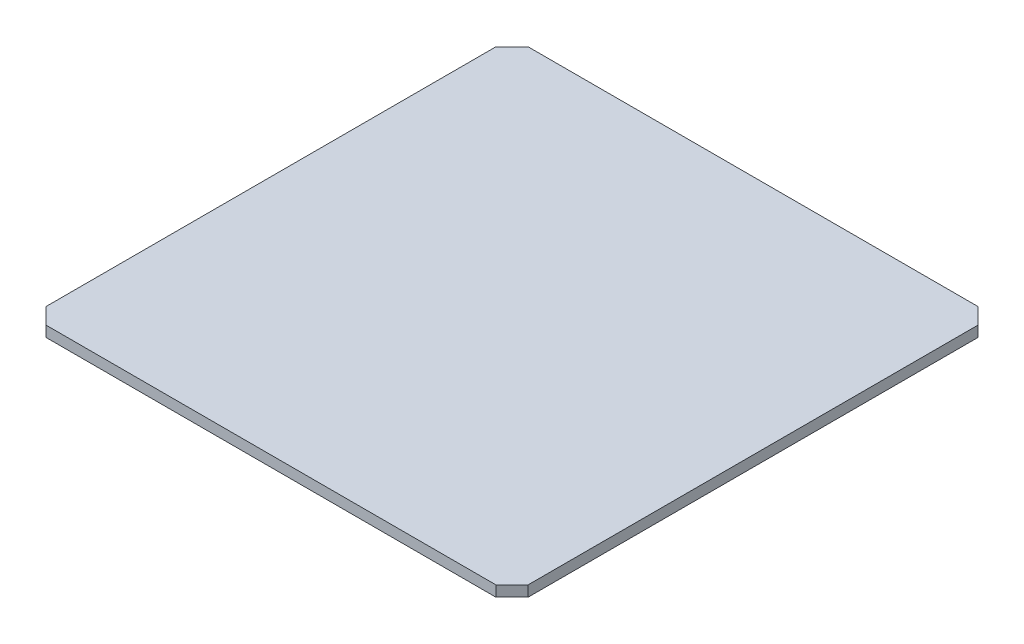
SolidWorks part; units mm, degrees
ref_plane "Front Plane" through (0, 0, 0) normal (0, 0, 1) x (1, 0, 0)
ref_plane "Top Plane" through (0, 0, 0) normal (0, 1, 0) x (1, 0, 0)
ref_plane "Right Plane" through (0, 0, 0) normal (1, 0, 0) x (0, 0, -1)
sketch "Esquisse1" plane through (0, 0, 0) normal (0, 1, 0) x (1, 0, 0)
  line L0 (45, 45) -> (-45, -45) construction
  line L1 (-42, 45) -> (42, 45)
  line L2 (-45, 42) -> (-45, -42)
  line L3 (-42, -45) -> (42, -45)
  line L4 (45, 42) -> (45, -42)
  line L5 (-45, 42) -> (-42, 45)
  line L6 (42, 45) -> (45, 42)
  line L7 (42, -45) -> (45, -42)
  line L8 (-45, -42) -> (-42, -45)
  point P0 (-45, 45)
  point P1 (45, -45)
  point P7 (-42, 38.7285)
  dimension "D1" = 90
extrude "Boss.-Extru.1" add sketch "Esquisse1" along normal blind 2
sketch "Esquisse2" plane through (0, 0, 0) normal (0, -1, 0) x (1, 0, 0)
  line L0 (24.5, 24.5) -> (-24.5, -24.5) construction
  line L1 (-24.5, 24.5) -> (24.5, 24.5) construction
  line L2 (-24.5, 24.5) -> (-24.5, -24.5) construction
  line L3 (-24.5, -24.5) -> (24.5, -24.5) construction
  line L4 (24.5, 24.5) -> (24.5, -24.5) construction
  circle A0 centre (-24.5, 24.5) radius 4
  circle A1 centre (24.5, 24.5) radius 4
  circle A2 centre (-24.5, -24.5) radius 4
  circle A3 centre (24.5, -24.5) radius 4
  circle A4 centre (-24.5, 24.5) radius 1.5
  circle A5 centre (24.5, 24.5) radius 1.5
  circle A6 centre (24.5, -24.5) radius 1.5
  circle A7 centre (-24.5, -24.5) radius 1.5
  dimension "D1" = 3
  dimension "D3" = 8
  dimension "D2" = 20.5
extrude "Boss.-Extru.2" add sketch "Esquisse2" along normal blind 6.25
sketch "Esquisse3" plane through (0, 0, 0) normal (0, -1, 0) x (1, 0, 0)
  line L0 (-7.5, -3.75) -> (7.5, 3.75) construction
  line L1 (-7.5, 3.75) -> (7.5, 3.75)
  line L2 (-7.5, 3.75) -> (-7.5, -3.75)
  line L3 (-7.5, -3.75) -> (7.5, -3.75)
  line L4 (7.5, 3.75) -> (7.5, -3.75)
  dimension "D1" = 15
  dimension "D2" = 7.5
extrude "Boss.-Extru.3" add sketch "Esquisse3" along normal blind 10
